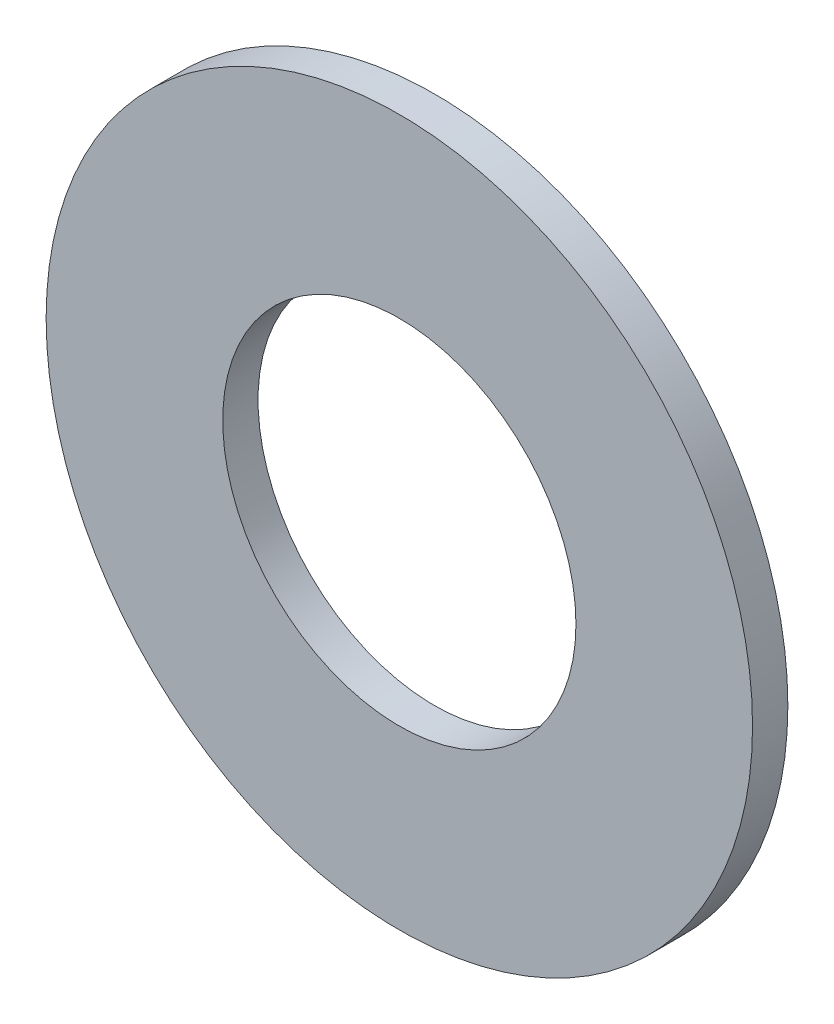
SolidWorks part; units mm, degrees
material "1.0503 (C45)"
ref_plane "前视基准面" through (0, 0, 0) normal (0, 0, 1) x (1, 0, 0)
ref_plane "上视基准面" through (0, 0, 0) normal (0, 1, 0) x (1, 0, 0)
ref_plane "右视基准面" through (0, 0, 0) normal (1, 0, 0) x (0, 0, -1)
other "Configuration Table"
sketch "草图1" plane through (0, 0, 0) normal (0, 0, 1) x (1, 0, 0)
  line L0 (-9.098, 0) -> (2.1323, 0) construction
  line L1 (0, 3.9004) -> (0, -3.1541) construction
  circle A0 centre (0, 0) radius 2.5
  circle A1 centre (0, 0) radius 5
  dimension "D1" = 5
  dimension "D2" = 10
extrude "凸台-拉伸1" add sketch "草图1" along normal blind 0.5
